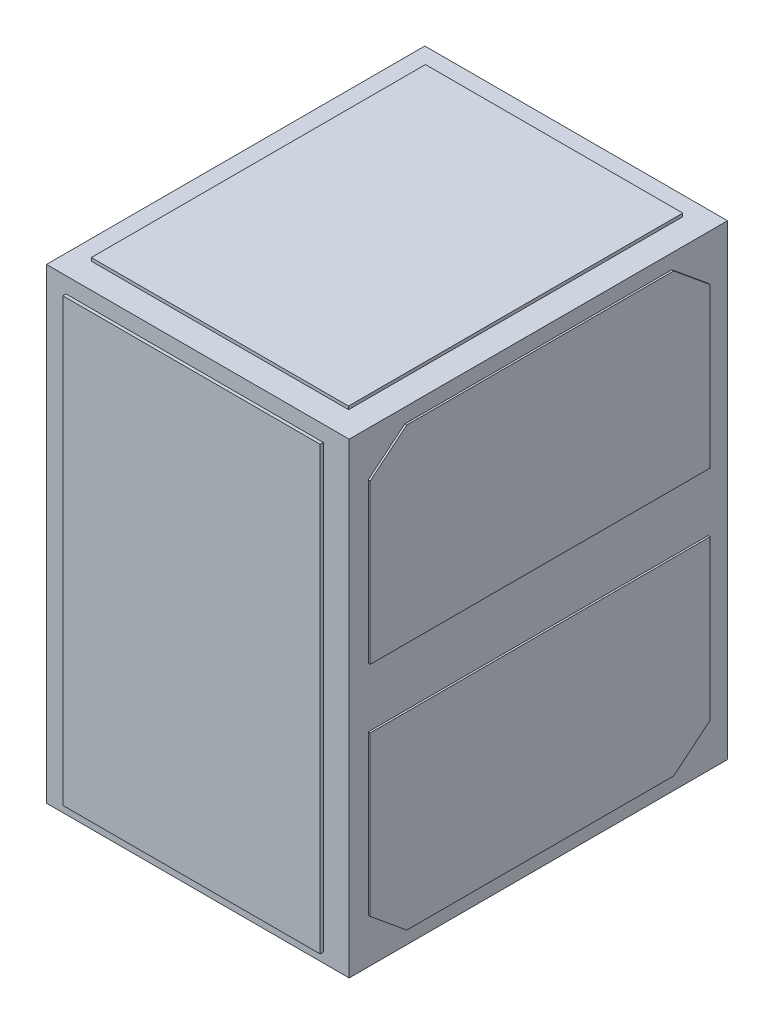
SolidWorks part; units mm, degrees
ref_plane "Front Plane" through (0, 0, 0) normal (0, 0, 1) x (1, 0, 0)
ref_plane "Top Plane" through (0, 0, 0) normal (0, 1, 0) x (1, 0, 0)
ref_plane "Right Plane" through (0, 0, 0) normal (1, 0, 0) x (0, 0, -1)
sketch "Sketch1" plane through (0, 0, 0) normal (0, 1, 0) x (1, 0, 0)
  line L1 (-120, -150) -> (120, -150)
  line L2 (-120, -150) -> (-120, 150)
  line L3 (-120, 150) -> (120, 150)
  line L4 (120, -150) -> (120, 150)
  line L5 (-120, -150) -> (120, 150) construction
  line L6 (-120, 150) -> (120, -150) construction
  point P0 (0, 0)
  dimension "D1" = 300
  dimension "D2" = 240
extrude "Boss-Extrude1" add sketch "Sketch1" along normal blind 370
sketch "Sketch2" plane through (0, 370, 0) normal (0, 1, 0) x (1, 0, 0)
  line L0 (0, 150) -> (0, -150) construction
  line L1 (120, 150) -> (-120, 150) construction
  line L2 (-120, -150) -> (120, -150) construction
  line L3 (-120, 0) -> (120, 0) construction
  line L4 (-120, 150) -> (-120, -150) construction
  line L5 (120, -150) -> (120, 150) construction
  circle A0 centre (-86, 120) radius 4.3
  circle A1 centre (86, 120) radius 4.3
  circle A2 centre (86, -120) radius 4.3
  circle A3 centre (-86, -120) radius 4.3
  dimension "D3" = 8.6
  dimension "D1" = 86
  dimension "D2" = 120
extrude "Boss-Extrude2" add sketch "Sketch2" along normal blind 2.5
sketch "Sketch3" plane through (0, 372.5, 0) normal (0, 1, 0) x (1, 0, 0)
  line L1 (102, -132.5) -> (-102, -132.5)
  line L2 (102, -132.5) -> (102, 132.5)
  line L3 (102, 132.5) -> (-102, 132.5)
  line L4 (-102, -132.5) -> (-102, 132.5)
  line L5 (102, -132.5) -> (-102, 132.5) construction
  line L6 (102, 132.5) -> (-102, -132.5) construction
  point P0 (0, 0)
  dimension "D1" = 265
  dimension "D2" = 204
extrude "Boss-Extrude3" add sketch "Sketch3" along normal blind 2.5
sketch "Sketch8" plane through (0, 0, 0) normal (0, -1, 0) x (1, 0, 0)
  circle A0 centre (-86, 120) radius 4.2861
  circle A1 centre (86, 120) radius 4.2861
  circle A2 centre (86, -120) radius 4.2861
  circle A3 centre (-86, -120) radius 4.2861
extrude "Boss-Extrude6" add sketch "Sketch8" along normal blind 2.5
sketch "Sketch9" plane through (0, -2.5, 0) normal (0, -1, 0) x (1, 0, 0)
  line L1 (-102, -132.5) -> (102, -132.5)
  line L2 (-102, -132.5) -> (-102, 132.5)
  line L3 (-102, 132.5) -> (102, 132.5)
  line L4 (102, -132.5) -> (102, 132.5)
  line L5 (-102, -132.5) -> (102, 132.5) construction
  line L6 (-102, 132.5) -> (102, -132.5) construction
  point P0 (0, 0)
extrude "Boss-Extrude7" add sketch "Sketch9" along normal blind 2.5
sketch "Sketch10" plane through (0, 0, 150) normal (0, 0, 1) x (1, 0, 0)
  line L0 (0, 370) -> (0, 0) construction
  line L1 (-120, 370) -> (120, 370) construction
  line L2 (-120, 185) -> (120, 185) construction
  line L3 (-120, 370) -> (-120, 0) construction
  line L4 (120, 370) -> (120, 0) construction
  circle A0 centre (-86, 345) radius 4.3
  circle A1 centre (86, 345) radius 4.3
  circle A2 centre (86, 25) radius 4.3
  circle A3 centre (-86, 25) radius 4.3
  dimension "D1" = 8.6
  dimension "D2" = 86
  dimension "D3" = 160
extrude "Boss-Extrude8" add sketch "Sketch10" along normal blind 2.5
sketch "Sketch12" plane through (0, 0, 152.5) normal (0, 0, 1) x (1, 0, 0)
  line L0 (0, 370) -> (0, 0) construction
  line L5 (-120, 370) -> (120, 370) construction
  line L6 (-120, 185) -> (120, 185) construction
  line L7 (-120, 370) -> (-120, 0) construction
  line L8 (120, 370) -> (120, 0) construction
  line L10 (-102, 10) -> (102, 10)
  line L11 (-102, 10) -> (-102, 360)
  line L12 (-102, 360) -> (102, 360)
  line L13 (102, 10) -> (102, 360)
  line L14 (-102, 10) -> (102, 360) construction
  line L15 (-102, 360) -> (102, 10) construction
  point P0 (1.6893, 185)
  point P12 (0, 185)
  dimension "D1" = 204
  dimension "D2" = 350
extrude "Boss-Extrude9" add sketch "Sketch12" along normal blind 2.5
sketch "Sketch13" plane through (0, 0, -150) normal (0, 0, -1) x (-1, 0, 0)
  circle A0 centre (-86, 345) radius 4.3
  circle A1 centre (86, 345) radius 4.3
  circle A2 centre (-86, 25) radius 4.3
  circle A3 centre (86, 25) radius 4.3
extrude "Boss-Extrude10" add sketch "Sketch13" along normal blind 2.5
sketch "Sketch14" plane through (0, 0, -152.5) normal (0, 0, -1) x (-1, 0, 0)
  line L1 (102, 10) -> (-102, 10)
  line L2 (102, 10) -> (102, 360)
  line L3 (102, 360) -> (-102, 360)
  line L4 (-102, 10) -> (-102, 360)
  line L5 (102, 10) -> (-102, 360) construction
  line L6 (102, 360) -> (-102, 10) construction
  point P0 (0, 185)
extrude "Boss-Extrude11" add sketch "Sketch14" along normal blind 2.5
sketch "Sketch15" plane through (-120, 0, 0) normal (-1, 0, 0) x (0, 0, 1)
  line L0 (-150, 185) -> (150, 185) construction
  line L1 (-150, 370) -> (-150, 0) construction
  line L2 (150, 370) -> (150, 0) construction
  line L3 (0, 370) -> (0, 0) construction
  line L4 (-150, 370) -> (150, 370) construction
  line L5 (-134.7882, 161.4554) -> (134.7882, 161.4554)
  line L6 (-134.7882, 161.4554) -> (-134.7882, 35.4554)
  line L7 (-134.7882, 35.4554) -> (-105.8555, 11.5986)
  line L8 (-105.8555, 11.5986) -> (105.8555, 11.5986)
  line L9 (134.7882, 35.4554) -> (105.8555, 11.5986)
  line L10 (134.7882, 161.4554) -> (134.7882, 35.4554)
  line L11 (-134.7882, 334.5446) -> (-105.8555, 358.4014)
  line L12 (-134.7882, 208.5446) -> (-134.7882, 334.5446)
  line L13 (-134.7882, 208.5446) -> (134.7882, 208.5446)
  line L14 (134.7882, 208.5446) -> (134.7882, 334.5446)
  line L15 (134.7882, 334.5446) -> (105.8555, 358.4014)
  line L16 (-105.8555, 358.4014) -> (105.8555, 358.4014)
  point P17 (0, 11.5986)
  point P19 (0, 161.4554)
  dimension "D1" = 126
  dimension "D2" = 37.5
  dimension "D3" = 105.8555
  dimension "D4" = 134.7882
extrude "Boss-Extrude12" add sketch "Sketch15" along normal blind 1.5
sketch "Sketch17" plane through (120, 0, 0) normal (1, 0, 0) x (0, 0, -1)
  line L0 (-134.7882, 208.5446) -> (134.7882, 208.5446)
  line L1 (134.7882, 208.5446) -> (134.7882, 334.5446)
  line L2 (134.7882, 334.5446) -> (105.8555, 358.4014)
  line L3 (105.8555, 358.4014) -> (-105.8555, 358.4014)
  line L4 (-105.8555, 358.4014) -> (-134.7882, 334.5446)
  line L5 (-134.7882, 334.5446) -> (-134.7882, 208.5446)
  line L6 (-134.7882, 161.4554) -> (134.7882, 161.4554)
  line L7 (134.7882, 161.4554) -> (134.7882, 35.4554)
  line L8 (134.7882, 35.4554) -> (105.8555, 11.5986)
  line L9 (105.8555, 11.5986) -> (-105.8555, 11.5986)
  line L10 (-105.8555, 11.5986) -> (-134.7882, 35.4554)
  line L11 (-134.7882, 35.4554) -> (-134.7882, 161.4554)
extrude "Boss-Extrude13" add sketch "Sketch17" along normal blind 1.5
